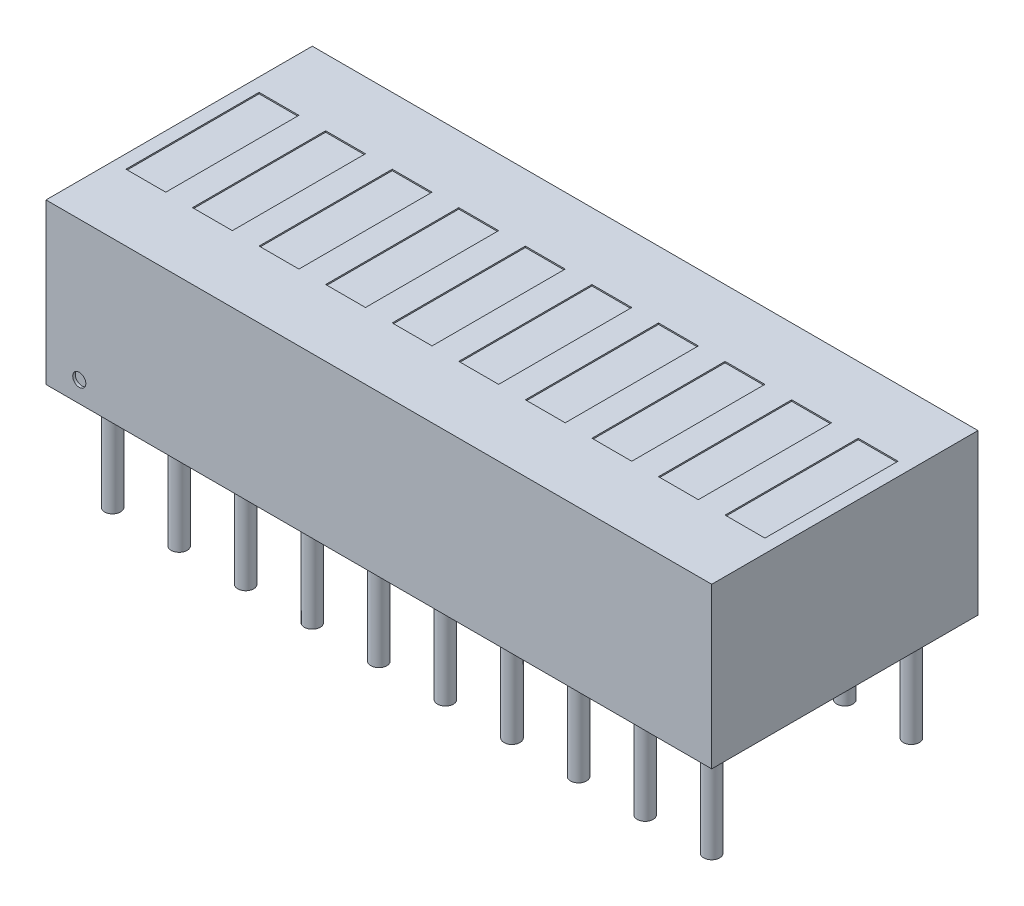
SolidWorks part; units mm, degrees
ref_plane "Front Plane" through (0, 0, 0) normal (0, 0, 1) x (1, 0, 0)
ref_plane "Top Plane" through (0, 0, 0) normal (0, 1, 0) x (1, 0, 0)
ref_plane "Right Plane" through (0, 0, 0) normal (1, 0, 0) x (0, 0, -1)
sketch "Sketch1" plane through (0, 0, 0) normal (0, 1, 0) x (1, 0, 0)
  line L1 (-12.7, -5.08) -> (12.7, -5.08)
  line L2 (-12.7, -5.08) -> (-12.7, 5.08)
  line L3 (-12.7, 5.08) -> (12.7, 5.08)
  line L4 (12.7, -5.08) -> (12.7, 5.08)
  line L5 (-12.7, -5.08) -> (12.7, 5.08) construction
  line L6 (-12.7, 5.08) -> (12.7, -5.08) construction
  point P0 (0, 0)
  dimension "D1" = 25.4
  dimension "D2" = 10.16
extrude "Boss-Extrude1" add sketch "Sketch1" along normal blind 6.1
sketch "Sketch2" plane through (0, 6.1, 0) normal (0, 1, 0) x (1, 0, 0)
  line L0 (0, 6.7973) -> (0, -7.2275) construction
  line L1 (-14.283, 0) -> (13.1645, 0) construction
  line L2 (-3.05, 2.54) -> (-3.05, -2.54)
  line L3 (-0.51, 2.54) -> (-2.03, 2.54)
  line L4 (-0.51, 2.54) -> (-0.51, -2.54)
  line L5 (-0.51, -2.54) -> (-2.03, -2.54)
  line L6 (-2.03, 2.54) -> (-2.03, -2.54)
  line L7 (-0.51, 2.54) -> (-2.03, -2.54) construction
  line L8 (-0.51, -2.54) -> (-2.03, 2.54) construction
  line L9 (-3.05, 2.54) -> (-4.57, 2.54)
  line L10 (-4.57, 2.54) -> (-4.57, -2.54)
  line L11 (-3.05, -2.54) -> (-4.57, -2.54)
  line L12 (-5.59, 2.54) -> (-5.59, -2.54)
  line L13 (-5.59, 2.54) -> (-7.11, 2.54)
  line L14 (-7.11, 2.54) -> (-7.11, -2.54)
  line L15 (-5.59, -2.54) -> (-7.11, -2.54)
  line L16 (-8.13, 2.54) -> (-8.13, -2.54)
  line L17 (-8.13, 2.54) -> (-9.65, 2.54)
  line L18 (-9.65, 2.54) -> (-9.65, -2.54)
  line L19 (-8.13, -2.54) -> (-9.65, -2.54)
  line L20 (-10.67, 2.54) -> (-10.67, -2.54)
  line L21 (-10.67, 2.54) -> (-12.19, 2.54)
  line L22 (-12.19, 2.54) -> (-12.19, -2.54)
  line L23 (-10.67, -2.54) -> (-12.19, -2.54)
  line L24 (10.67, 2.54) -> (12.19, 2.54)
  line L25 (12.19, 2.54) -> (12.19, -2.54)
  line L26 (10.67, -2.54) -> (12.19, -2.54)
  line L27 (10.67, 2.54) -> (10.67, -2.54)
  line L28 (8.13, 2.54) -> (9.65, 2.54)
  line L29 (9.65, 2.54) -> (9.65, -2.54)
  line L30 (8.13, -2.54) -> (9.65, -2.54)
  line L31 (8.13, 2.54) -> (8.13, -2.54)
  line L32 (5.59, 2.54) -> (7.11, 2.54)
  line L33 (7.11, 2.54) -> (7.11, -2.54)
  line L34 (5.59, -2.54) -> (7.11, -2.54)
  line L35 (5.59, 2.54) -> (5.59, -2.54)
  line L36 (3.05, 2.54) -> (4.57, 2.54)
  line L37 (4.57, 2.54) -> (4.57, -2.54)
  line L38 (3.05, -2.54) -> (4.57, -2.54)
  line L39 (3.05, 2.54) -> (3.05, -2.54)
  line L40 (0.51, -2.54) -> (2.03, -2.54)
  line L41 (2.03, 2.54) -> (2.03, -2.54)
  line L42 (0.51, 2.54) -> (2.03, 2.54)
  line L43 (0.51, 2.54) -> (0.51, -2.54)
  point P5 (-1.27, 0)
  dimension "D1" = 1.52
  dimension "D2" = 5.08
  dimension "D3" = 1.27
  dimension "D4" = 5
extrude "Cut-Extrude1" cut sketch "Sketch2" against normal blind 0.05
sketch "Sketch3" plane through (0, 0, 0) normal (0, -1, 0) x (1, 0, 0)
  line L0 (-13.6234, 0) -> (13.8241, 0) construction
  line L1 (0, 6.7113) -> (0, -7.2849) construction
  circle A0 centre (-1.27, 3.81) radius 0.305
  circle A1 centre (-3.81, 3.81) radius 0.305
  circle A2 centre (-6.35, 3.81) radius 0.305
  circle A3 centre (-8.89, 3.81) radius 0.305
  circle A4 centre (-11.43, 3.81) radius 0.305
  circle A5 centre (-3.81, -3.81) radius 0.305
  circle A6 centre (-6.35, -3.81) radius 0.305
  circle A7 centre (-8.89, -3.81) radius 0.305
  circle A8 centre (-11.43, -3.81) radius 0.305
  circle A9 centre (-1.27, -3.81) radius 0.305
  circle A10 centre (11.43, -3.81) radius 0.305
  circle A11 centre (8.89, -3.81) radius 0.305
  circle A12 centre (6.35, -3.81) radius 0.305
  circle A13 centre (3.81, -3.81) radius 0.305
  circle A14 centre (1.27, -3.81) radius 0.305
  circle A15 centre (1.27, 3.81) radius 0.305
  circle A16 centre (3.81, 3.81) radius 0.305
  circle A17 centre (6.35, 3.81) radius 0.305
  circle A18 centre (8.89, 3.81) radius 0.305
  circle A19 centre (11.43, 3.81) radius 0.305
  dimension "D1" = 0.61
  dimension "D2" = 1.27
  dimension "D3" = 3.81
  dimension "D4" = 5
  dimension "D5" = 2
extrude "Boss-Extrude2" add sketch "Sketch3" along normal blind 4.06
sketch "Sketch4" plane through (0, 0, 5.08) normal (0, 0, 1) x (1, 0, 0)
  line L0 (-11.43, -4.06) -> (-11.43, 2.8308) construction
  line L1 (-11.735, -4.06) -> (-11.125, -4.06) construction
  circle A0 centre (-11.43, 0.7902) radius 0.25
  dimension "D1" = 0.5
extrude "Cut-Extrude2" cut sketch "Sketch4" against normal blind 0.1
